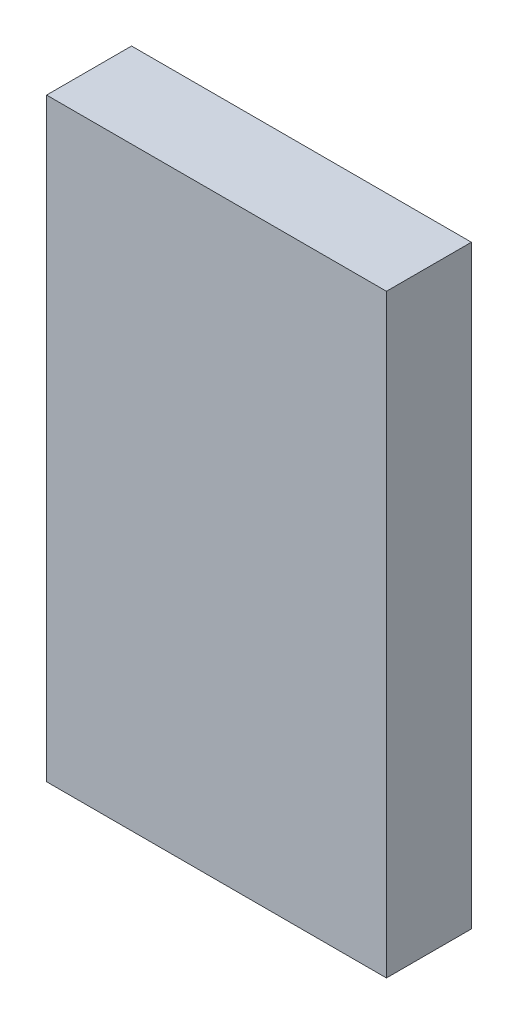
SolidWorks part; units mm, degrees
ref_plane "Front Plane" through (0, 0, 0) normal (0, 0, 1) x (1, 0, 0)
ref_plane "Top Plane" through (0, 0, 0) normal (0, 1, 0) x (1, 0, 0)
ref_plane "Right Plane" through (0, 0, 0) normal (1, 0, 0) x (0, 0, -1)
sketch "Sketch1" plane through (0, 0, 0) normal (0, 0, 1) x (1, 0, 0)
  line L1 (-12.7, -22.225) -> (12.7, -22.225)
  line L2 (-12.7, -22.225) -> (-12.7, 22.225)
  line L3 (-12.7, 22.225) -> (12.7, 22.225)
  line L4 (12.7, -22.225) -> (12.7, 22.225)
  line L5 (-12.7, -22.225) -> (12.7, 22.225) construction
  line L6 (-12.7, 22.225) -> (12.7, -22.225) construction
  point P0 (0, 0)
  dimension "D1" = 25.4
  dimension "D2" = 44.45
extrude "Boss-Extrude1" add sketch "Sketch1" along normal blind 6.35
